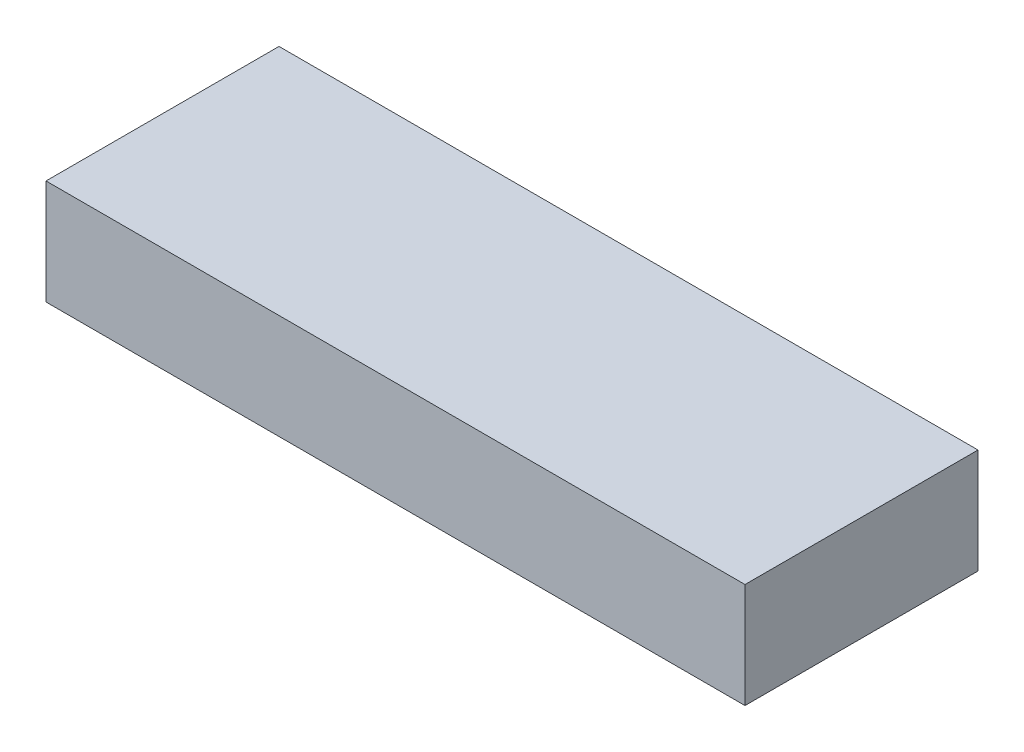
SolidWorks part; units mm, degrees
ref_plane "Front Plane" through (0, 0, 0) normal (0, 0, 1) x (1, 0, 0)
ref_plane "Top Plane" through (0, 0, 0) normal (0, 1, 0) x (1, 0, 0)
ref_plane "Right Plane" through (0, 0, 0) normal (1, 0, 0) x (0, 0, -1)
sketch "Sketch2" plane through (0, 0, 0) normal (0, 1, 0) x (1, 0, 0)
  line L1 (0, 0) -> (-15.24, 0)
  line L2 (0, 0) -> (0, 5.08)
  line L3 (0, 5.08) -> (-15.24, 5.08)
  line L4 (-15.24, 0) -> (-15.24, 5.08)
  dimension "D1" = 5.08
  dimension "D2" = 15.24
extrude "Boss-Extrude1" add sketch "Sketch2" along normal blind 2.286
